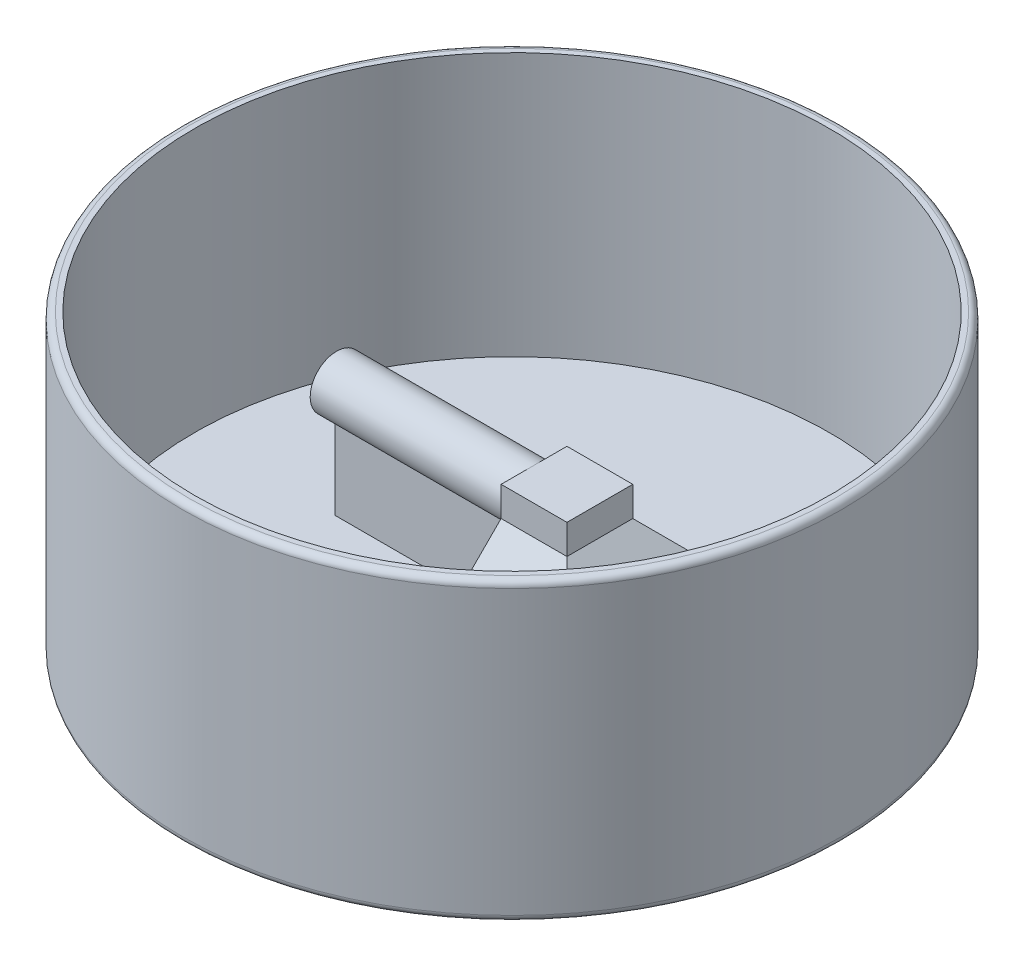
SolidWorks part; units mm, degrees
ref_plane "Front Plane" through (0, 0, 0) normal (0, 0, 1) x (1, 0, 0)
ref_plane "Top Plane" through (0, 0, 0) normal (0, 1, 0) x (1, 0, 0)
ref_plane "Right Plane" through (0, 0, 0) normal (1, 0, 0) x (0, 0, -1)
sketch "Sketch1" plane through (0, 0, 0) normal (0, 1, 0) x (1, 0, 0)
  circle A0 centre (0, 0) radius 50.05
  dimension "D1" = 100.1
extrude "Boss-Extrude1" add sketch "Sketch1" along normal blind 45
sketch "Sketch3" plane through (0, 45, 0) normal (0, 1, 0) x (1, 0, 0)
  circle A0 centre (0, 0) radius 48.25
  dimension "D1" = 96.5
extrude "Cut-Extrude2" cut sketch "Sketch3" against normal blind 40
sketch "Sketch4" plane through (0, 5, 0) normal (0, 1, 0) x (1, 0, 0)
  line L1 (13.3461, 5) -> (3.3461, 5)
  line L2 (13.3461, 5) -> (13.3461, -5)
  line L3 (13.3461, -5) -> (3.3461, -5)
  line L4 (3.3461, 5) -> (3.3461, -5)
  line L5 (13.3461, 5) -> (3.3461, -5) construction
  line L6 (13.3461, -5) -> (3.3461, 5) construction
  point P0 (8.3461, 0)
  dimension "D1" = 10
  dimension "D2" = 10
extrude "Boss-Extrude2" add sketch "Sketch4" along normal blind 21.5
sketch "Sketch5" plane through (3.3461, 0, 0) normal (-1, 0, 0) x (0, 0, 1)
  line L1 (-50.05, 0) -> (50.05, 0) construction
  circle A0 centre (0, 22.5) radius 4
  dimension "D1" = 8
  dimension "D2" = 22.5
extrude "Boss-Extrude3" add sketch "Sketch5" along normal blind 30
sketch "Sketch6" plane through (0, 5, 0) normal (0, 1, 0) x (1, 0, 0)
  line L0 (-26.6539, 4) -> (-26.6539, -4) construction
  line L1 (-26.6539, 0) -> (1.5308, 0)
  line L2 (-26.6539, 0) -> (-26.6539, -0.2)
  line L3 (-26.6539, -0.2) -> (1.5308, -0.2)
  line L4 (1.5308, 0) -> (1.5308, -0.2)
  dimension "D1" = 0.2
extrude "Boss-Extrude4" add sketch "Sketch6" along normal up to next
fillet "Fillet1" radius 1 2 edges at (0, 0, 50.05) (0, 45, 50.05)
chamfer "Chamfer1" distance 17 angle 45 3 edges at (13.3461, 5, 0) (8.3461, 5, -5) (8.3461, 5, 5)
sketch "Sketch7" plane through (0, 0, 0) normal (0, 0, 1) x (1, 0, 0)
  line L1 (-22.9241, 23.163) -> (-18.3576, 23.163)
  line L2 (-22.9241, 23.163) -> (-22.9241, 22.0193)
  line L3 (-22.9241, 22.0193) -> (-18.3576, 22.0193)
  line L4 (-18.3576, 23.163) -> (-18.3576, 22.0193)
  line L5 (-12.5968, 23.163) -> (-7.9367, 23.163)
  line L6 (-12.5968, 23.163) -> (-12.5968, 21.9153)
  line L7 (-12.5968, 21.9153) -> (-7.9367, 21.9153)
  line L8 (-7.9367, 23.163) -> (-7.9367, 21.9153)
  line L9 (-3.7438, 22.9551) -> (-0.4867, 22.9551)
  line L10 (-3.7438, 22.9551) -> (-3.7438, 21.9153)
  line L11 (-3.7438, 21.9153) -> (-0.4867, 21.9153)
  line L12 (-0.4867, 22.9551) -> (-0.4867, 21.9153)
  line L13 (6.7574, 18.1723) -> (9.0448, 18.1723)
  line L14 (6.7574, 18.1723) -> (6.7574, 16.5088)
  line L15 (6.7574, 16.5088) -> (9.0448, 16.5088)
  line L16 (9.0448, 18.1723) -> (9.0448, 16.5088)
  line L17 (12.5799, 18.1723) -> (14.9713, 18.1723)
  line L18 (12.5799, 18.1723) -> (12.5799, 16.1968)
  line L19 (12.5799, 16.1968) -> (14.9713, 16.1968)
  line L20 (14.9713, 18.1723) -> (14.9713, 16.1968)
  line L25 (2.7416, 22.8655) -> (4.437, 22.8655)
  line L26 (2.7416, 22.8655) -> (2.7416, 21.8258)
  line L27 (2.7416, 21.8258) -> (4.437, 21.8258)
  line L28 (4.437, 22.8655) -> (4.437, 21.8258)
  line L29 (6.1504, 20.6501) -> (7.5515, 20.6501)
  line L30 (6.1504, 20.6501) -> (6.1504, 20.193)
  line L31 (6.1504, 20.193) -> (7.5515, 20.193)
  line L32 (7.5515, 20.6501) -> (7.5515, 20.193)
extrude "Cut-Extrude3" cut sketch "Sketch7" against normal blind 0.2
